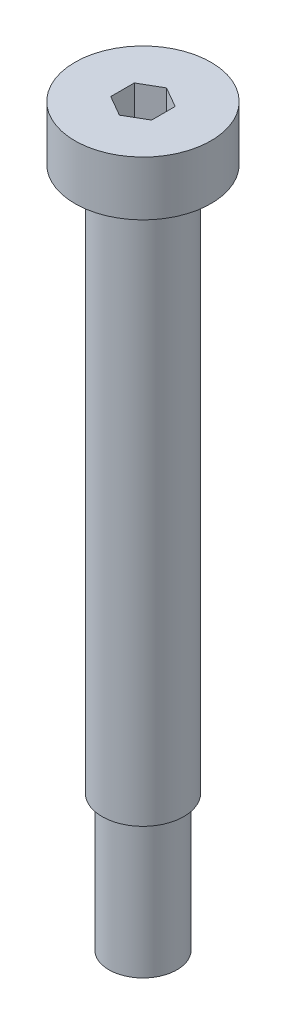
SolidWorks part; units mm, degrees
ref_plane "Front Plane" through (0, 0, 0) normal (0, 0, 1) x (1, 0, 0)
ref_plane "Top Plane" through (0, 0, 0) normal (0, 1, 0) x (1, 0, 0)
ref_plane "Right Plane" through (0, 0, 0) normal (1, 0, 0) x (0, 0, -1)
sketch "Sketch1" plane through (0, 0, 0) normal (0, 0, 1) x (1, 0, 0)
  line L0 (0, 0) -> (0, -64) construction
  line L1 (0, 0) -> (-5, 0)
  line L2 (-5, 0) -> (-5, -4)
  line L3 (-5, -4) -> (-3, -4)
  line L4 (-3, -4) -> (-3, -54)
  line L5 (-3, -54) -> (-2.25, -54)
  line L6 (-2.25, -54) -> (-2.25, -64)
  line L7 (-2.25, -64) -> (0, -64)
  line L8 (0, 0) -> (0, -64)
  dimension "D1" = 5
  dimension "D2" = 10
  dimension "D3" = 50
  dimension "D4" = 4
  dimension "D5" = 3
  dimension "D6" = 2.25
revolve "Revolve1" [suppressed] add sketch "Sketch1" angle 360 about L0
sketch "Sketch2" [suppressed] plane through (0, 0, 0) normal (0, 1, 0) x (1, 0, 0)
  line L1 (1.5, 0.866) -> (0, 1.7321)
  line L2 (0, 1.7321) -> (-1.5, 0.866)
  line L3 (-1.5, 0.866) -> (-1.5, -0.866)
  line L4 (-1.5, -0.866) -> (0, -1.7321)
  line L5 (0, -1.7321) -> (1.5, -0.866)
  line L6 (1.5, -0.866) -> (1.5, 0.866)
  circle A0 centre (0, 0) radius 1.5 construction
  dimension "D1" = 3
extrude "Cut-Extrude1" [suppressed] cut sketch "Sketch2" against normal blind 3
sketch "Sketch3" plane through (0, 0, 0) normal (0, 0, 1) x (1, 0, 0)
  line L0 (0, 0) -> (-5, 0)
  line L1 (-5, 0) -> (-5, -4)
  line L2 (-5, -4) -> (-3, -4)
  line L3 (-3, -4) -> (-3, -44)
  line L4 (-3, -44) -> (-2.5, -44)
  line L5 (-2.5, -44) -> (-2.5, -54)
  line L6 (-2.5, -54) -> (0, -54)
  line L7 (0, 0) -> (0, -54) construction
  line L8 (0, 0) -> (0, -54)
  dimension "D1" = 5
  dimension "D2" = 3
  dimension "D3" = 4
  dimension "D4" = 40
  dimension "D5" = 10
  dimension "D6" = 2.5
revolve "Revolve2" add sketch "Sketch3" angle 360 about L7
sketch "Sketch4" plane through (0, 0, 0) normal (0, 1, 0) x (1, 0, 0)
  line L1 (1.5, 0.866) -> (0, 1.7321)
  line L2 (0, 1.7321) -> (-1.5, 0.866)
  line L3 (-1.5, 0.866) -> (-1.5, -0.866)
  line L4 (-1.5, -0.866) -> (0, -1.7321)
  line L5 (0, -1.7321) -> (1.5, -0.866)
  line L6 (1.5, -0.866) -> (1.5, 0.866)
  circle A0 centre (0, 0) radius 1.5 construction
  point P1 (0, 0)
  dimension "D1" = 3
extrude "Cut-Extrude2" cut sketch "Sketch4" against normal blind 3
